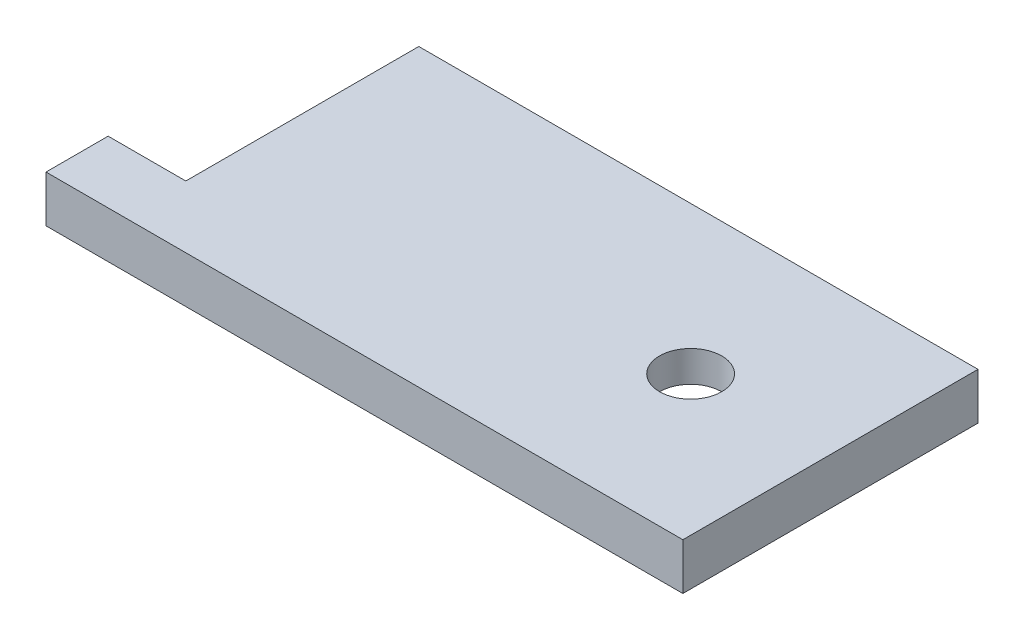
SolidWorks part; units mm, degrees
ref_plane "Přední rovina" through (0, 0, 0) normal (0, 0, 1) x (1, 0, 0)
ref_plane "Horní rovina" through (0, 0, 0) normal (0, 1, 0) x (1, 0, 0)
ref_plane "Pravá rovina" through (0, 0, 0) normal (1, 0, 0) x (0, 0, -1)
sketch "Skica1" plane through (0, 0, 0) normal (0, 0, 1) x (1, 0, 0)
  line L0 (0, 0) -> (0, 7)
  line L1 (0, 7) -> (4, 7)
  line L2 (4, 7) -> (4, 3)
  line L3 (4, 3) -> (36, 3)
  line L4 (36, 3) -> (36, 0)
  line L5 (36, 0) -> (0, 0)
  dimension "D1" = 4
  dimension "D2" = 36
  dimension "D3" = 4
  dimension "D4" = 3
extrude "Přidat vysunutím1" add sketch "Skica1" along normal blind 19
sketch "Skica2" plane through (0, 0, 19) normal (0, 0, 1) x (1, 0, 0)
  line L1 (0, 7) -> (4, 7)
  line L2 (0, 7) -> (0, 3)
  line L3 (0, 3) -> (4, 3)
  line L4 (4, 7) -> (4, 3)
extrude "Odebrat vysunutím1" cut sketch "Skica2" against normal blind 15
sketch "Skica3" plane through (0, 0, 0) normal (0, -1, 0) x (1, 0, 0)
  line L0 (0, 19) -> (0, 0) construction
  line L1 (2, 17) -> (34, 17)
  line L2 (2, 17) -> (2, 2)
  line L3 (2, 2) -> (34, 2)
  line L4 (34, 17) -> (34, 2)
  line L5 (0, 19) -> (36, 19) construction
  dimension "D1" = 2
  dimension "D2" = 2
  dimension "D3" = 15
  dimension "D4" = 32
extrude "Odebrat vysunutím2" cut sketch "Skica3" against normal blind 1
sketch "Skica4" plane through (0, 0, 0) normal (-1, 0, 0) x (0, 0, 1)
  line L1 (0, 7) -> (4, 7)
  line L2 (0, 7) -> (0, 3)
  line L3 (0, 3) -> (4, 3)
  line L4 (4, 7) -> (4, 3)
extrude "Odebrat vysunutím3" cut sketch "Skica4" against normal blind 50
sketch "Skica5" plane through (0, 0, 0) normal (-1, 0, 0) x (0, 0, 1)
  line L0 (19, 0) -> (0, 0) construction
  line L1 (0, 3) -> (4, 3)
  line L2 (0, 3) -> (0, 0)
  line L3 (0, 0) -> (4, 0)
  line L4 (4, 3) -> (4, 0)
  dimension "D1" = 4
extrude "Přidat vysunutím2" add sketch "Skica5" along normal blind 5
sketch "Skica6" plane through (0, 1, 0) normal (0, -1, 0) x (1, 0, 0)
  line L0 (34, 2) -> (34, 17) construction
  line L2 (34, 17) -> (2, 17) construction
  circle A0 centre (27, 9.5) radius 2
  dimension "D1" = 4
  dimension "D2" = 7
  dimension "D3" = 7.5
extrude "Odebrat vysunutím4" cut sketch "Skica6" against normal blind 5
sketch "Skica8" plane through (-5, 0, 0) normal (-1, 0, 0) x (0, 0, 1)
  line L1 (0, 3) -> (4, 3)
  line L2 (0, 3) -> (0, 0)
  line L3 (0, 0) -> (4, 0)
  line L4 (4, 3) -> (4, 0)
extrude "Odebrat vysunutím6" cut sketch "Skica8" against normal blind 5
sketch "Skica9" plane through (0, 0, 0) normal (-1, 0, 0) x (0, 0, 1)
  line L0 (0, 3) -> (19, 3) construction
  line L1 (19, 0) -> (15, 0)
  line L2 (19, 0) -> (19, 3)
  line L3 (19, 3) -> (15, 3)
  line L4 (15, 0) -> (15, 3)
  dimension "D1" = 4
extrude "Přidat vysunutím3" add sketch "Skica9" along normal blind 5
